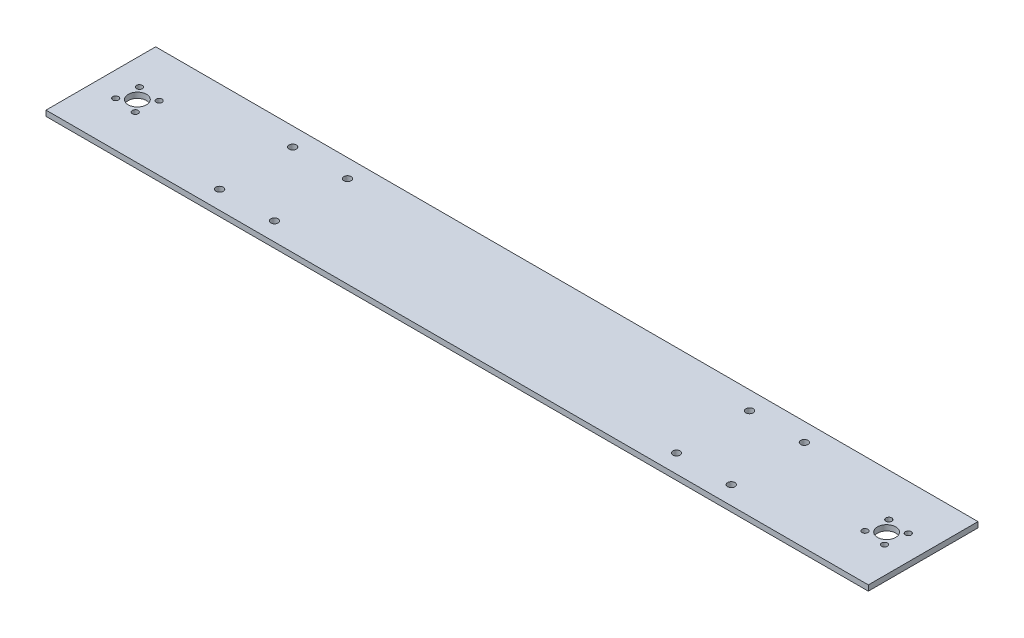
SolidWorks part; units mm, degrees
material "3.0515 (EN-AW 3103)"
ref_plane "Płaszczyzna przednia" through (0, 0, 0) normal (0, 0, 1) x (1, 0, 0)
ref_plane "Płaszczyzna górna" through (0, 0, 0) normal (0, 1, 0) x (1, 0, 0)
ref_plane "Płaszczyzna prawa" through (0, 0, 0) normal (1, 0, 0) x (0, 0, -1)
sketch "Szkic1" plane through (0, 0, 0) normal (0, 1, 0) x (1, 0, 0)
  line L1 (0, 0) -> (-450, 0)
  line L2 (0, 0) -> (0, 60)
  line L3 (0, 60) -> (-450, 60)
  line L4 (-450, 0) -> (-450, 60)
  dimension "D1" = 60
  dimension "D2" = 450
extrude "Dodanie-wyciągnięcie1" add sketch "Szkic1" along normal blind 3
hole_wizard "Otwór pod śrubę M41" positions "Szkic6" profile "Szkic7" hole size "M4" standard "Ansi Metric" end condition through all
sketch "Szkic6" plane through (0, 3, 0) normal (0, 1, 0) x (1, 0, 0)
  line L0 (0, 60) -> (-450, 60) construction
  line L1 (-450, 0) -> (0, 0) construction
  line L2 (-450, 60) -> (-450, 0) construction
  line L3 (0, 0) -> (0, 60) construction
  point P0 (-365, 50)
  point P2 (-335, 50)
  point P4 (-365, 10)
  point P6 (-335, 10)
  point P8 (-115, 50)
  point P10 (-85, 50)
  point P12 (-115, 10)
  point P14 (-85, 10)
  dimension "D1" = 10
  dimension "D2" = 10
  dimension "D3" = 30
  dimension "D4" = 30
  dimension "D5" = 30
  dimension "D6" = 30
  dimension "D7" = 85
  dimension "D8" = 85
  dimension "D9" = 85
  dimension "D10" = 85
sketch "Szkic7" plane through (-365, 3, -50) normal (1, 0, 0) x (0, 0, 1)
  line L0 (0, 0) -> (0, 3)
  line L1 (0, 3) -> (2, 3)
  line L2 (2, 3) -> (2, 0)
  line L5 (2, 0) -> (0, 0)
  line L11 (0, -6.35) -> (0, 107.95) construction
  dimension "Œrednica otworu na wylot" = 4
  dimension "G³êbokoœæ otworu na wylot" = 3
sketch "Szkic8" plane through (0, 3, 0) normal (0, 1, 0) x (1, 0, 0)
  line L0 (0, 60) -> (-450, 60) construction
  line L2 (0, 0) -> (0, 60) construction
  line L3 (-450, 60) -> (-450, 0) construction
  circle A0 centre (-20, 30) radius 5
  circle A1 centre (-430, 30) radius 5
  dimension "D1" = 10
  dimension "D2" = 30
  dimension "D3" = 20
  dimension "D4" = 10
  dimension "D5" = 30
  dimension "D6" = 20
extrude "Wytnij-wyciągnięcie1" cut sketch "Szkic8" against normal blind 10
sketch "Szkic9" plane through (0, 3, 0) normal (0, 1, 0) x (1, 0, 0)
  circle A0 centre (-435.3563, 36.5109) radius 1.6
  circle A1 centre (-436.5109, 24.6437) radius 1.6
  circle A2 centre (-424.6437, 23.4891) radius 1.6
  circle A3 centre (-423.4891, 35.3563) radius 1.6
extrude "Wytnij-wyciągnięcie2" cut sketch "Szkic9" against normal through all
sketch "Szkic10" plane through (0, 3, 0) normal (0, 1, 0) x (1, 0, 0)
  circle A0 centre (-13.4891, 35.3563) radius 1.6
  circle A1 centre (-14.6437, 23.4891) radius 1.6
  circle A2 centre (-26.5109, 24.6437) radius 1.6
  circle A4 centre (-25.3457, 36.555) radius 1.6
  point P11 (-25.4083, 36.4548)
  point P12 (-25.3457, 36.555)
  point P13 (0, 0)
  dimension "D1" = 3.2
extrude "Wytnij-wyciągnięcie3" cut sketch "Szkic10" against normal blind 10
